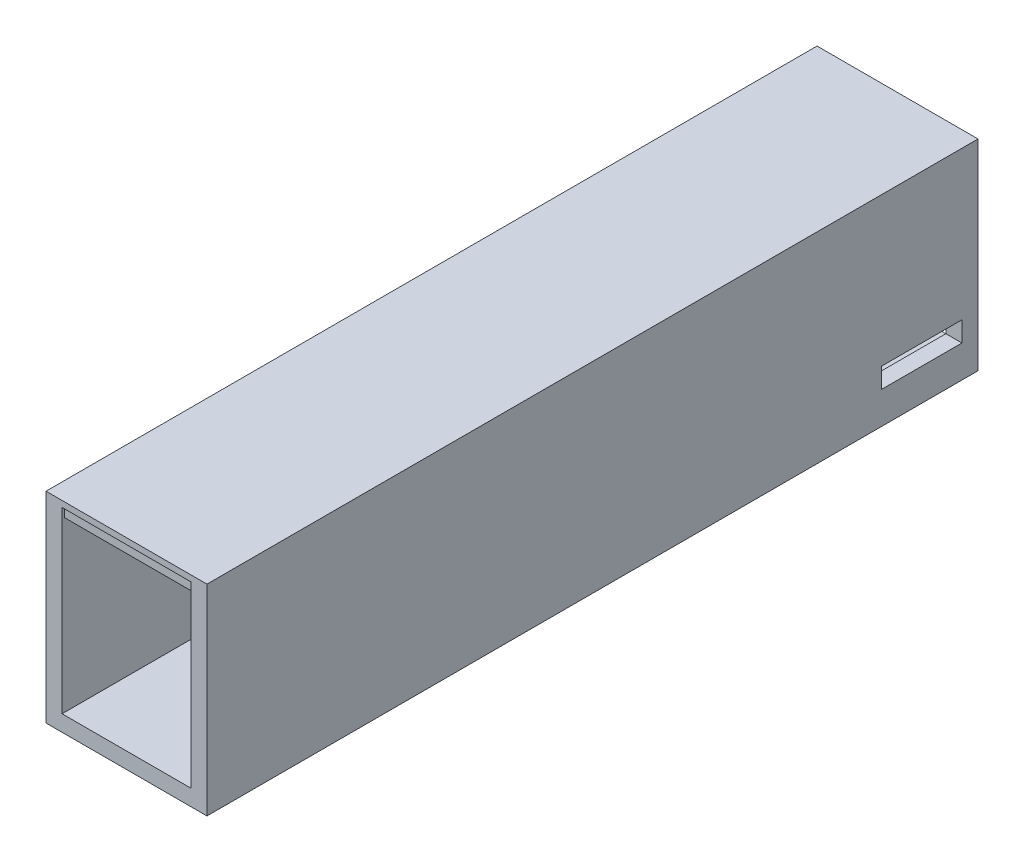
SolidWorks part; units mm, degrees
ref_plane "Front Plane" through (0, 0, 0) normal (0, 0, 1) x (1, 0, 0)
ref_plane "Top Plane" through (0, 0, 0) normal (0, 1, 0) x (1, 0, 0)
ref_plane "Right Plane" through (0, 0, 0) normal (1, 0, 0) x (0, 0, -1)
sketch "Sketch1" plane through (0, 0, 0) normal (0, 0, 1) x (1, 0, 0)
  line L0 (-62.7006, -99.9557) -> (137.6994, -99.9557)
  line L1 (137.6994, -99.9557) -> (137.6994, 150.0443)
  line L2 (-62.7006, 150.0443) -> (-62.7006, -99.9557)
  line L3 (112.6994, -74.9557) -> (112.6994, -54.5557)
  line L4 (-37.7006, -74.9557) -> (112.6994, -74.9557)
  line L5 (112.6994, -54.5557) -> (-37.7006, -54.5557)
  line L6 (-37.7006, -54.5557) -> (-37.7006, -74.9557)
  line L7 (49.9994, 7.9443) -> (49.9994, 32.9443)
  line L8 (24.9994, 32.9443) -> (24.9994, 7.9443)
  line L9 (24.9994, 7.9443) -> (49.9994, 7.9443)
  line L10 (49.9994, 32.9443) -> (24.9994, 32.9443)
  line L11 (-62.7006, 150.0443) -> (137.6994, 150.0443)
  line L12 (-42.7006, 130.0443) -> (-42.7006, -79.9557)
  line L13 (-42.7006, -79.9557) -> (117.6994, -79.9557)
  line L14 (117.6994, -79.9557) -> (117.6994, 130.0443)
  line L15 (-42.7006, 130.0443) -> (117.6994, 130.0443)
sketch "Sketch2" plane through (0, 0, 0) normal (0, 0, 1) x (1, 0, 0)
  line L0 (-42.7006, 130.0443) -> (-42.7006, -79.9557) construction
  line L1 (-42.7006, -79.9557) -> (117.6994, -79.9557) construction
  line L2 (117.6994, -79.9557) -> (117.6994, 130.0443) construction
  line L3 (-42.7006, 130.0443) -> (117.6994, 130.0443) construction
  line L4 (-62.7006, 150.0443) -> (-62.7006, -99.9557) construction
  line L5 (-62.7006, -99.9557) -> (137.6994, -99.9557) construction
  line L6 (137.6994, -99.9557) -> (137.6994, 150.0443) construction
  line L7 (-62.7006, 150.0443) -> (137.6994, 150.0443) construction
  line L8 (-42.7006, 130.0443) -> (-42.7006, -79.9557)
  line L9 (-42.7006, -79.9557) -> (117.6994, -79.9557)
  line L10 (117.6994, -79.9557) -> (117.6994, 130.0443)
  line L11 (-42.7006, 130.0443) -> (117.6994, 130.0443)
  line L12 (-62.7006, 150.0443) -> (-62.7006, -99.9557)
  line L13 (-62.7006, -99.9557) -> (137.6994, -99.9557)
  line L14 (137.6994, -99.9557) -> (137.6994, 150.0443)
  line L15 (-62.7006, 150.0443) -> (137.6994, 150.0443)
extrude "Boss-Extrude1" add sketch "Sketch2" along normal mid plane 960
sketch "Sketch3" plane through (0, 0, 480) normal (0, 0, 1) x (1, 0, 0)
  line L0 (117.6994, -79.9557) -> (117.6994, 130.0443) construction
  line L1 (-42.7006, 142.5443) -> (117.6994, 142.5443)
  line L2 (-42.7006, 142.5443) -> (-42.7006, 117.5443)
  line L3 (-42.7006, 117.5443) -> (117.6994, 117.5443)
  line L4 (117.6994, 142.5443) -> (117.6994, 117.5443)
  line L5 (-42.7006, 130.0443) -> (-42.7006, -79.9557) construction
  line L6 (117.6994, 130.0443) -> (-42.7006, 130.0443) construction
  point P8 (-42.7006, 130.0443)
  dimension "D1" = 25
extrude "Cut-Extrude1" cut sketch "Sketch3" against normal blind 3
mirror "Mirror1" about plane through (0, 0, 0) normal (0, 0, 1) of "Cut-Extrude1"
sketch "Sketch4" plane through (-42.7006, 0, 0) normal (1, 0, 0) x (0, 0, -1)
  line L0 (480, 142.5443) -> (480, -79.9557) construction
  line L1 (360, -34.9557) -> (460, -34.9557)
  line L2 (360, -34.9557) -> (360, -59.9557)
  line L3 (360, -59.9557) -> (460, -59.9557)
  line L4 (460, -34.9557) -> (460, -59.9557)
  line L6 (-480, -79.9557) -> (480, -79.9557) construction
  dimension "D1" = 20
  dimension "D2" = 20
  dimension "D3" = 100
  dimension "D4" = 25
extrude "Cut-Extrude2" cut sketch "Sketch4" against normal through all both and the other way through all
sketch "Sketch5" plane through (0, -99.9557, 0) normal (0, -1, 0) x (1, 0, 0)
  line L1 (137.9994, 45) -> (157.9994, 45)
  line L2 (137.9994, 45) -> (137.9994, -45)
  line L3 (137.9994, -45) -> (157.9994, -45)
  line L4 (-62.7006, -480) -> (137.6994, -480)
  line L5 (137.6994, -480) -> (137.6994, 480)
  line L6 (137.6994, 480) -> (-62.7006, 480)
  line L7 (-62.7006, 480) -> (-62.7006, -480)
  line L8 (-62.7006, -480) -> (137.6994, -480) construction
  line L9 (137.6994, -480) -> (137.6994, 480) construction
  line L10 (137.6994, 480) -> (-62.7006, 480) construction
  line L11 (-62.7006, 480) -> (-62.7006, -480) construction
  line L12 (157.9994, 45) -> (157.9994, -45)
  line L13 (-63.0006, 45) -> (-83.0006, 45)
  line L14 (-63.0006, 45) -> (-63.0006, -45)
  line L15 (-63.0006, -45) -> (-83.0006, -45)
  line L16 (-83.0006, 45) -> (-83.0006, -45)
  line L17 (-83.0006, -12.5) -> (157.9994, -12.5) construction
  line L18 (-83.0006, -12.5) -> (-83.0006, 12.5) construction
  line L19 (-83.0006, 12.5) -> (157.9994, 12.5) construction
  line L20 (157.9994, -12.5) -> (157.9994, 12.5) construction
  line L21 (-83.0006, -12.5) -> (157.9994, 12.5) construction
  line L22 (-83.0006, 12.5) -> (157.9994, -12.5) construction
  circle A0 centre (37.4994, 0) radius 128.6283
  circle A1 centre (37.4994, 0) radius 55
  circle A2 centre (37.4994, 0) radius 48.4
  point P12 (157.9994, 0)
  point P14 (37.4994, 0)
  point P25 (37.4994, 480)
  dimension "D5" = 110
  dimension "D2" = 90
  dimension "D3" = 20
  dimension "D4" = 25
  dimension "D7" = 201
  dimension "D1" = 0
  dimension "D6" = 6.6
sketch "Sketch7" plane through (0, -99.9557, 0) normal (0, -1, 0) x (1, 0, 0)
  line L0 (-37.5006, 0) -> (112.4994, 0) construction
  circle A0 centre (112.4994, 0) radius 1.5
  circle A1 centre (-37.5006, 0) radius 1.5
  point P4 (37.4994, 0)
  dimension "D1" = 3
  dimension "D2" = 150
extrude "Cut-Extrude4" cut sketch "Sketch7" against normal blind 20
sketch "Door locking mechanism" plane through (137.6994, 0, 0) normal (1, 0, 0) x (0, 0, -1)
  line L0 (-480, -99.9557) -> (-480, 150.0443) construction
  line L1 (-480, 80.0443) -> (-489, 80.0443)
  line L2 (-480, 80.0443) -> (-480, -99.9557)
  line L3 (-480, -99.9557) -> (-489, -99.9557)
  line L4 (-489, 80.0443) -> (-489, -99.9557)
  line L5 (-480, -99.9557) -> (480, -99.9557) construction
  line L6 (-480, 35.0443) -> (-455, 35.0443) construction
  line L7 (-480, 45.0443) -> (-483, 45.0443)
  line L8 (-480, 45.0443) -> (-480, 25.0443)
  line L9 (-480, 25.0443) -> (-483, 25.0443)
  line L10 (-483, 45.0443) -> (-483, 25.0443)
  line L11 (-480, 20.0443) -> (-476, 20.0443)
  line L12 (-480, 20.0443) -> (-480, 50.0443)
  line L13 (-480, 50.0443) -> (-476, 50.0443)
  line L14 (-476, 20.0443) -> (-476, 50.0443)
  line L15 (-476, 47.5443) -> (-455, 47.5443)
  line L16 (-476, 47.5443) -> (-476, 22.5443)
  line L17 (-476, 22.5443) -> (-455, 22.5443)
  line L18 (-455, 47.5443) -> (-455, 22.5443)
  line L19 (-480, 22.5443) -> (-480, 47.5443)
  line L20 (-477.5, 25.0443) -> (-457.5, 25.0443)
  line L21 (-477.5, 25.0443) -> (-477.5, 45.0443)
  line L22 (-477.5, 45.0443) -> (-457.5, 45.0443)
  line L23 (-457.5, 25.0443) -> (-457.5, 45.0443)
  line L24 (-477.5, 25.0443) -> (-457.5, 45.0443) construction
  line L25 (-477.5, 45.0443) -> (-457.5, 25.0443) construction
  line L26 (-480, 47.5443) -> (-455, 47.5443)
  line L27 (-455, 22.5443) -> (-455, 47.5443)
  line L28 (-480, 22.5443) -> (-455, 22.5443)
  line L29 (-464.55, 36.7474) -> (-467.5, 38.4506)
  line L30 (-464.75, 36.632) -> (-467.5, 38.2197) construction
  line L31 (-467.5, 38.2197) -> (-470.25, 36.632) construction
  line L32 (-470.25, 36.632) -> (-470.25, 33.4565) construction
  line L33 (-470.25, 33.4565) -> (-467.5, 31.8688) construction
  line L34 (-467.5, 31.8688) -> (-464.75, 33.4565) construction
  line L35 (-464.75, 33.4565) -> (-464.75, 36.632) construction
  line L36 (-467.5, 38.4506) -> (-470.45, 36.7474)
  line L37 (-470.45, 36.7474) -> (-470.45, 33.3411)
  line L38 (-470.45, 33.3411) -> (-467.5, 31.6379)
  line L39 (-467.5, 31.6379) -> (-464.55, 33.3411)
  line L40 (-464.55, 33.3411) -> (-464.55, 36.7474)
  circle A0 centre (-467.5, 35.0443) radius 2.5
  circle A1 centre (-467.5, 35.0443) radius 6.5
  circle A2 centre (-467.5, 35.0443) radius 2.75 construction
  point P16 (-476, 35.0443)
  point P17 (-483, 35.0443)
  point P22 (-455, 35.0443)
  point P25 (-467.5, 35.0443)
  dimension "D12" = 5
  dimension "D1" = 9
  dimension "D2" = 180
  dimension "D3" = 3
  dimension "D4" = 20
  dimension "D5" = 35
  dimension "D6" = 4
  dimension "D7" = 30
  dimension "D8" = 25
  dimension "D9" = 21
  dimension "D10" = 20
  dimension "D11" = 2.5
  dimension "D14" = 5.5
  dimension "D13" = 4
  dimension "D15" = 0.2
sketch "Slot guider" plane through (137.6994, 0, 0) normal (1, 0, 0) x (0, 0, -1)
  line L0 (-465.5, 43.4943) -> (-457.25, 43.4943)
  line L1 (-455, 45.7443) -> (-480, 45.7443) construction
  line L2 (-455, 45.7443) -> (-455, 20.7443) construction
  line L3 (-455, 20.7443) -> (-480, 20.7443) construction
  line L4 (-480, 45.7443) -> (-480, 20.7443) construction
  line L5 (-480, -99.9557) -> (-480, 150.0443) construction
  line L6 (-454.8, 45.9443) -> (-480.2, 45.9443)
  line L7 (-480.2, 45.9443) -> (-480.2, 20.5443)
  line L8 (-454.8, 20.5443) -> (-480.2, 20.5443)
  line L9 (-454.8, 45.9443) -> (-454.8, 20.5443)
  line L10 (-477.75, 43.4943) -> (-469.5, 43.4943)
  line L11 (-477.5, 43.2443) -> (-457.5, 43.2443) construction
  line L12 (-477.5, 43.2443) -> (-477.5, 23.2443) construction
  line L13 (-477.5, 23.2443) -> (-457.5, 23.2443) construction
  line L14 (-457.5, 43.2443) -> (-457.5, 23.2443) construction
  line L15 (-457.25, 43.4943) -> (-457.25, 22.9943)
  line L16 (-477.75, 22.9943) -> (-469.5, 22.9943)
  line L17 (-477.75, 43.4943) -> (-477.75, 22.9943)
  line L18 (-467.5, 43.4943) -> (-467.5, 22.9943) construction
  line L19 (-469.5, 43.4943) -> (-469.5, 22.9943)
  line L20 (-465.5, 43.4943) -> (-465.5, 22.9943)
  line L21 (-477.75, 43.4943) -> (-457.25, 43.4943) construction
  line L22 (-480.2, 45.9443) -> (-483.2, 45.9443)
  line L23 (-480.2, 45.9443) -> (-480.2, 20.5443)
  line L24 (-480.2, 20.5443) -> (-483.2, 20.5443)
  line L25 (-483.2, 45.9443) -> (-483.2, 20.5443)
  line L26 (-465.5, 22.9943) -> (-457.25, 22.9943)
  line L27 (-477.75, 22.9943) -> (-457.25, 22.9943) construction
  circle A0 centre (-467.5, 33.2443) radius 1
  point P27 (-467.5, 33.2443)
  dimension "D6" = 3
  dimension "D1" = 0.2
  dimension "D2" = 0.25
  dimension "D4" = 2
  dimension "D5" = 2
